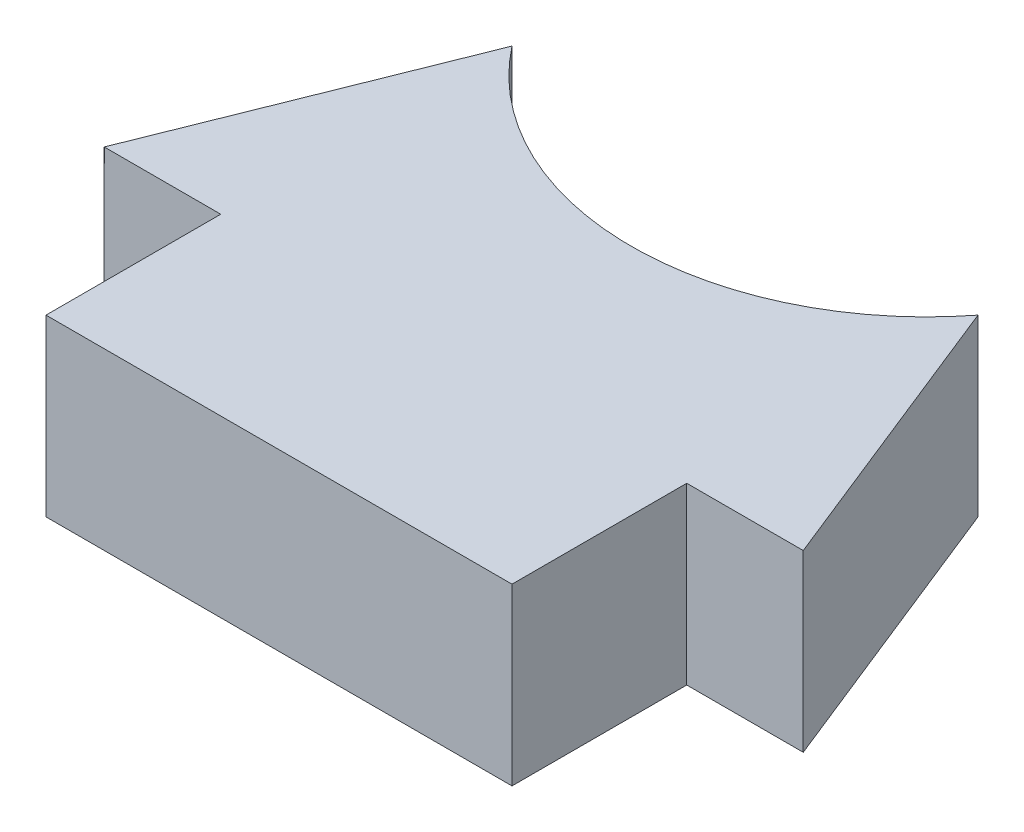
SolidWorks part; units mm, degrees
ref_plane "Plano frontal" through (0, 0, 0) normal (0, 0, 1) x (1, 0, 0)
ref_plane "Plano superior" through (0, 0, 0) normal (0, 1, 0) x (1, 0, 0)
ref_plane "Plano direito" through (0, 0, 0) normal (1, 0, 0) x (0, 0, -1)
sketch "Esboço1" plane through (0, 0, 0) normal (0, 1, 0) x (1, 0, 0)
  line L0 (-12.8322, -16.7536) -> (-4.8322, -16.7536)
  line L1 (-4.8322, -16.7536) -> (-4.8322, -13.7536)
  line L2 (-4.8322, -13.7536) -> (-2.8322, -13.7536)
  line L3 (-12.8322, -16.7536) -> (-12.8322, -13.7536)
  line L4 (-12.8322, -13.7536) -> (-14.8322, -13.7536)
  line L6 (-14.8322, -13.7536) -> (-12.8322, -8.7536)
  line L7 (-2.8322, -13.7536) -> (-4.8322, -8.7536)
  arc A0 (-4.8322, -8.7536) -> (-12.8322, -8.7536) centre (-8.8322, -5.6354) cw
extrude "Ressalto-extrusão1" add sketch "Esboço1" along normal blind 3
